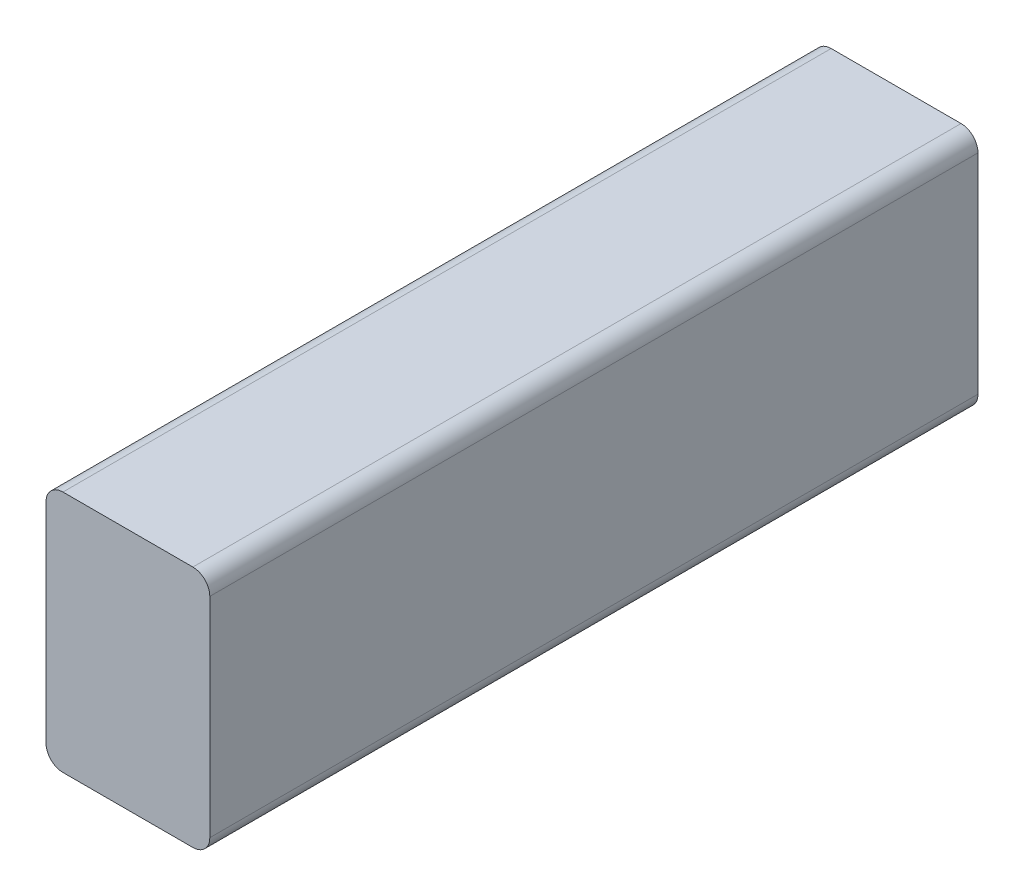
SolidWorks part; units mm, degrees
ref_plane "前视基准面" through (0, 0, 0) normal (0, 0, 1) x (1, 0, 0)
ref_plane "上视基准面" through (0, 0, 0) normal (0, 1, 0) x (1, 0, 0)
ref_plane "右视基准面" through (0, 0, 0) normal (1, 0, 0) x (0, 0, -1)
sketch "草图1" plane through (0, 0, 0) normal (0, 0, 1) x (1, 0, 0)
  line L1 (-14.5, 21.5) -> (14.5, 21.5)
  line L2 (-14.5, 21.5) -> (-14.5, -21.5)
  line L3 (-14.5, -21.5) -> (14.5, -21.5)
  line L4 (14.5, 21.5) -> (14.5, -21.5)
  line L5 (-14.5, 21.5) -> (14.5, -21.5) construction
  line L6 (-14.5, -21.5) -> (14.5, 21.5) construction
  point P0 (0, 0)
  dimension "D1" = 43
  dimension "D2" = 29
extrude "凸台-拉伸1" add sketch "草图1" along normal blind 136
fillet "圆角1" radius 3 4 edges at (14.5, -21.5, 68) (-14.5, -21.5, 68) (-14.5, 21.5, 68) (14.5, 21.5, 68)
